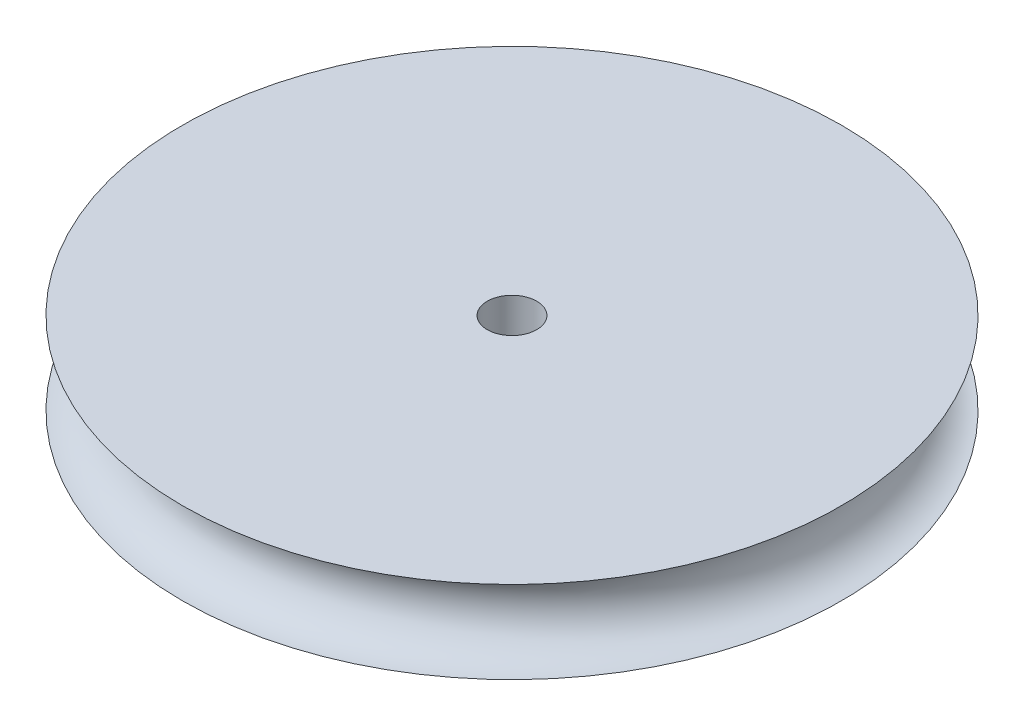
SolidWorks part; units mm, degrees
ref_plane "Front Plane" through (0, 0, 0) normal (0, 0, 1) x (1, 0, 0)
ref_plane "Top Plane" through (0, 0, 0) normal (0, 1, 0) x (1, 0, 0)
ref_plane "Right Plane" through (0, 0, 0) normal (1, 0, 0) x (0, 0, -1)
sketch "Sketch1" plane through (0, 0, 0) normal (0, 0, 1) x (1, 0, 0)
  line L0 (0, 0) -> (0, 5) construction
  line L1 (-1.5, 0) -> (-20, 0)
  line L2 (-1.5, 5) -> (-1.5, 0)
  line L3 (-20, 5) -> (-1.5, 5)
  arc A0 (-20, 0) -> (-20, 5) centre (-20, 2.5) ccw
  dimension "D2" = 5
  dimension "D1" = 5
  dimension "D3" = 20
  dimension "D4" = 1.5
revolve "Revolve1" add sketch "Sketch1" angle 360 about L0
